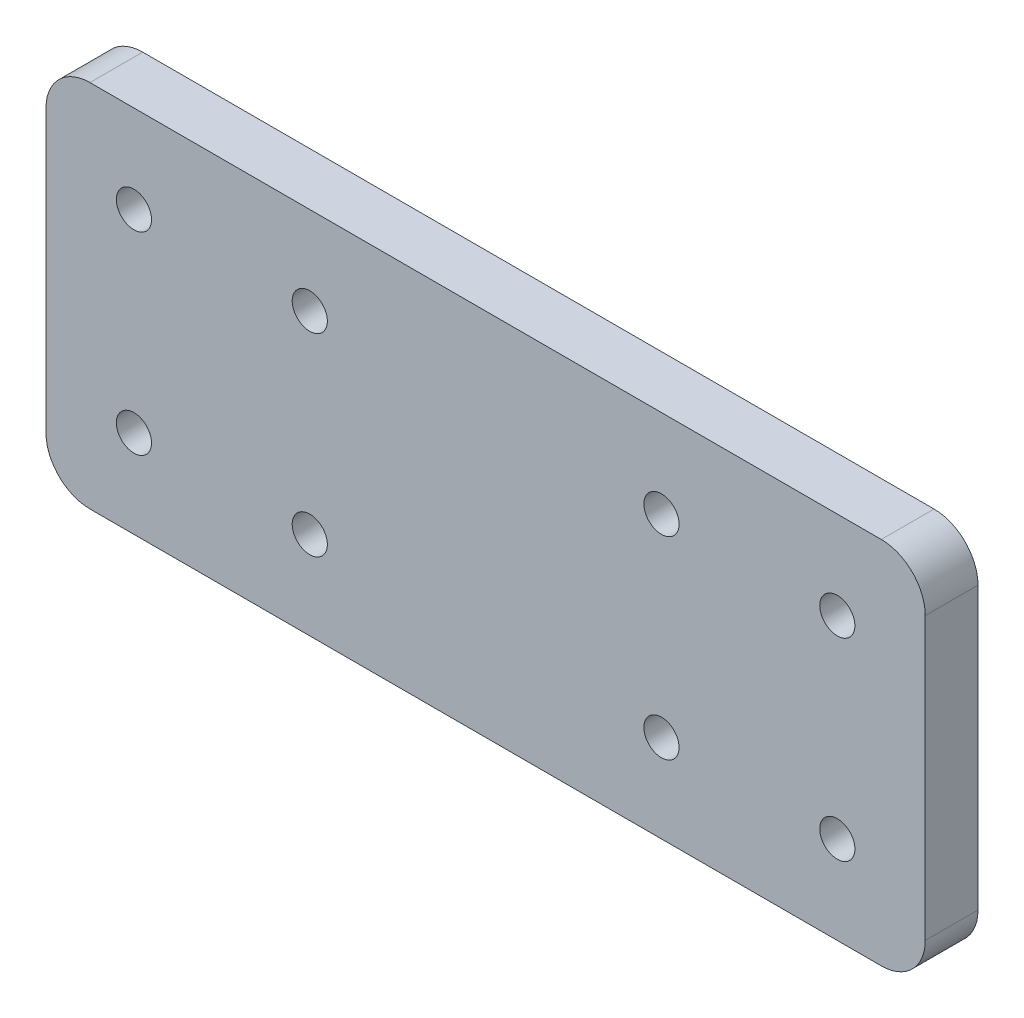
SolidWorks part; units mm, degrees
ref_plane "Спереди" through (0, 0, 0) normal (0, 0, 1) x (1, 0, 0)
ref_plane "Сверху" through (0, 0, 0) normal (0, 1, 0) x (1, 0, 0)
ref_plane "Справа" through (0, 0, 0) normal (1, 0, 0) x (0, 0, -1)
sketch "Эскиз1" plane through (0, 0, 0) normal (0, 0, 1) x (1, 0, 0)
  line L0 (0, 38.7755) -> (0, -42.517) construction
  line L1 (45, -21) -> (-45, -21)
  line L2 (50, -16) -> (50, 16)
  line L3 (45, 21) -> (-45, 21)
  line L4 (-50, -16) -> (-50, 16)
  line L5 (50, -21) -> (-50, 21) construction
  line L6 (50, 21) -> (-50, -21) construction
  line L7 (-57.483, 0) -> (57.1429, 0) construction
  circle A4 centre (-40, 11) radius 2
  circle A6 centre (-20, 11) radius 2
  circle A7 centre (-40, -11) radius 2
  circle A8 centre (-20, -11) radius 2
  circle A9 centre (20, -11) radius 2
  circle A10 centre (40, -11) radius 2
  circle A11 centre (40, 11) radius 2
  circle A12 centre (20, 11) radius 2
  arc A13 (45, -21) -> (50, -16) centre (45, -16) ccw
  arc A14 (50, 16) -> (45, 21) centre (45, 16) ccw
  arc A15 (-45, -21) -> (-50, -16) centre (-45, -16) cw
  arc A16 (-45, 21) -> (-50, 16) centre (-45, 16) ccw
  point P0 (0, 0)
  point P26 (0, 0)
  dimension "D6" = 10
  dimension "D3" = 4
  dimension "D4" = 10
  dimension "D7" = 5
  dimension "D1" = 100
  dimension "D2" = 42
  dimension "D5" = 20
extrude "Бобышка-Вытянуть1" add sketch "Эскиз1" along normal blind 6
